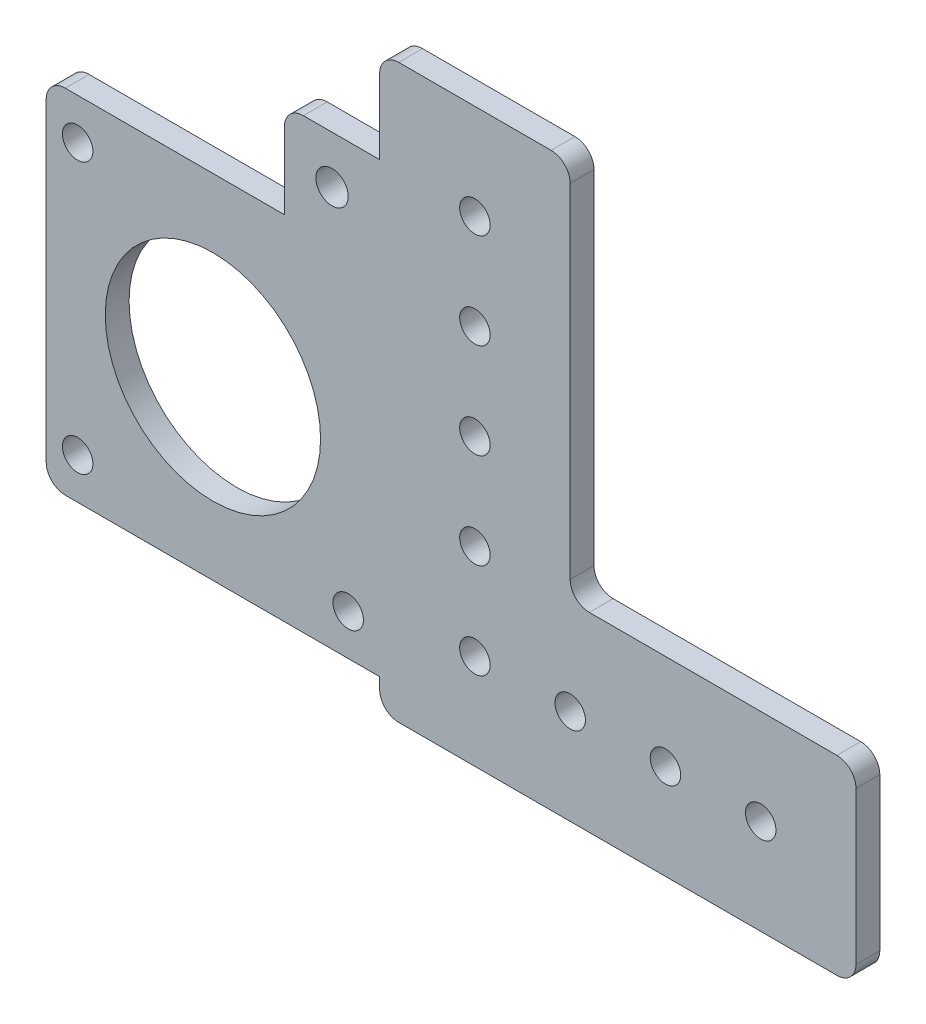
SolidWorks part; units mm, degrees
ref_plane "Front Plane" through (0, 0, 0) normal (0, 0, 1) x (1, 0, 0)
ref_plane "Top Plane" through (0, 0, 0) normal (0, 1, 0) x (1, 0, 0)
ref_plane "Right Plane" through (0, 0, 0) normal (1, 0, 0) x (0, 0, -1)
sketch "Sketch1" plane through (0, 0, 0) normal (0, 0, 1) x (1, 0, 0)
  line L0 (0, -38.1) -> (0, 38.1) construction
  line L1 (-12.7, -38.1) -> (12.7, -38.1)
  line L2 (-12.7, -38.1) -> (-12.7, 38.1)
  line L3 (-12.7, 38.1) -> (12.7, 38.1)
  line L4 (12.7, -38.1) -> (12.7, 38.1)
  line L5 (-12.7, -38.1) -> (12.7, 38.1) construction
  line L6 (-12.7, 38.1) -> (12.7, -38.1) construction
  line L7 (-34.925, 11.625) -> (-34.925, -32.825) construction
  line L8 (-55.88, -32.825) -> (-13.97, -32.825) construction
  line L9 (-12.7, 38.1) -> (-12.7, -38.1)
  line L10 (-55.88, -32.825) -> (-55.88, 11.625) construction
  line L11 (-55.88, 11.625) -> (-13.97, 11.625) construction
  line L12 (-12.7, -24.638) -> (-12.7, 24.638)
  line L13 (-13.97, -32.825) -> (-13.97, 11.625) construction
  line L14 (-55.88, -32.825) -> (-13.97, 11.625) construction
  line L15 (-55.88, 11.625) -> (-13.97, -32.825) construction
  line L16 (-57.15, -34.095) -> (-12.7, -34.095)
  line L17 (-57.15, -34.095) -> (-57.15, 12.895)
  line L18 (-57.15, 12.895) -> (-12.7, 12.895)
  line L19 (-12.7, -34.095) -> (-12.7, 12.895)
  line L20 (-57.15, -34.095) -> (-12.7, 12.895) construction
  line L21 (-57.15, 12.895) -> (-12.7, -34.095) construction
  circle A0 centre (-34.925, -10.6) radius 14.351
  circle A1 centre (-52.959, 7.434) radius 2.032
  circle A2 centre (-16.891, -28.634) radius 2.032
  circle A3 centre (-52.959, -28.634) radius 2.032
  circle A4 centre (-16.891, 7.434) radius 2.032 construction
  point P0 (0, 0)
  point P6 (-34.925, -10.6)
  point P9 (0, 0)
  point P16 (-34.925, -10.6)
  dimension "D5" = 1.27
  dimension "D10" = 18.034
  dimension "D7" = 4.064
  dimension "D12" = 28.702
  dimension "D1" = 76.2
  dimension "D2" = 25.4
  dimension "D3" = 41.91
  dimension "D4" = 44.45
  dimension "D6" = 1.27
  dimension "D8" = 18.034
  dimension "D9" = 18.034
  dimension "D11" = 18.034
  dimension "D13" = 27.5
extrude "Boss-Extrude1" add sketch "Sketch1" along normal blind 3.175
sketch "Sketch2" plane through (0, 0, 3.175) normal (0, 0, 1) x (1, 0, 0)
  line L0 (0, 38.1) -> (0, -38.1) construction
  line L1 (-12.7, 38.1) -> (12.7, 38.1) construction
  line L2 (-12.7, -38.1) -> (12.7, -38.1) construction
  circle A0 centre (0, 0) radius 2.032
  circle A1 centre (0, 12.7) radius 2.032
  circle A2 centre (0, 25.4) radius 2.032
  circle A3 centre (0, -12.7) radius 2.032
  circle A4 centre (0, -25.4) radius 2.032
  dimension "D1" = 4.064
  dimension "D2" = 3
  dimension "D3" = 3
extrude "Cut-Extrude1" cut sketch "Sketch2" against normal through all
sketch "Sketch4" plane through (12.7, 0, 0) normal (1, 0, 0) x (0, 0, -1)
  line L0 (0, -38.1) -> (0, 38.1) construction
  line L1 (-3.175, -38.1) -> (0, -38.1)
  line L2 (-3.175, -38.1) -> (-3.175, -12.7)
  line L3 (-3.175, -12.7) -> (0, -12.7)
  line L4 (0, -38.1) -> (0, -12.7)
  dimension "D1" = 25.4
extrude "Boss-Extrude2" add sketch "Sketch4" along normal blind 38.1
sketch "Sketch5" plane through (0, 0, 0) normal (0, 0, -1) x (-1, 0, 0)
  circle A0 centre (0, -25.4) radius 2.032 construction
  circle A1 centre (0, -25.4) radius 2.032
  circle A2 centre (-12.7, -25.4) radius 2.032
  circle A3 centre (-25.4, -25.4) radius 2.032
  circle A4 centre (-38.1, -25.4) radius 2.032
  dimension "D1" = 4
extrude "Cut-Extrude2" cut sketch "Sketch5" against normal through all
fillet "Fillet5" radius 2.54 9 edges at (-12.7, -38.1, 1.5875) (-57.15, -34.095, 1.5875) (-57.15, 12.895, 1.5875) (-12.7, 12.895, 1.5875) (-12.7, 38.1, 1.5875) (12.7, 38.1, 1.5875) (12.7, -12.7, 1.5875) (50.8, -12.7, 1.5875) (50.8, -38.1, 1.5875)
sketch "Sketch6" plane through (0, 0, 3.175) normal (0, 0, 1) x (1, 0, 0)
  line L0 (-15.24, 12.895) -> (-12.7, 12.895) construction
  line L1 (-12.7, 15.435) -> (-12.7, 12.895) construction
  line L2 (-54.61, 12.895) -> (-15.24, 12.895) construction
  line L3 (-12.7, 12.895) -> (-25.4, 12.895)
  line L4 (-12.7, 12.895) -> (-12.7, 25.595)
  line L5 (-12.7, 25.595) -> (-25.4, 25.595)
  line L6 (-25.4, 12.895) -> (-25.4, 25.595)
  arc A0 (-15.24, 12.895) -> (-12.7, 15.435) centre (-15.24, 15.435) ccw construction
  circle A1 centre (-19.05, 19.245) radius 2.159
  dimension "D1" = 4.318
  dimension "D2" = 6.35
  dimension "D3" = 6.35
  dimension "D4" = 12.7
  dimension "D5" = 12.7
extrude "Boss-Extrude3" add sketch "Sketch6" against normal up to surface (3.175 mm away) up to face at (10.668, -25.4, 0)
fillet "Fillet6" radius 2.54 1 edges at (-25.4, 25.595, 1.5875)
